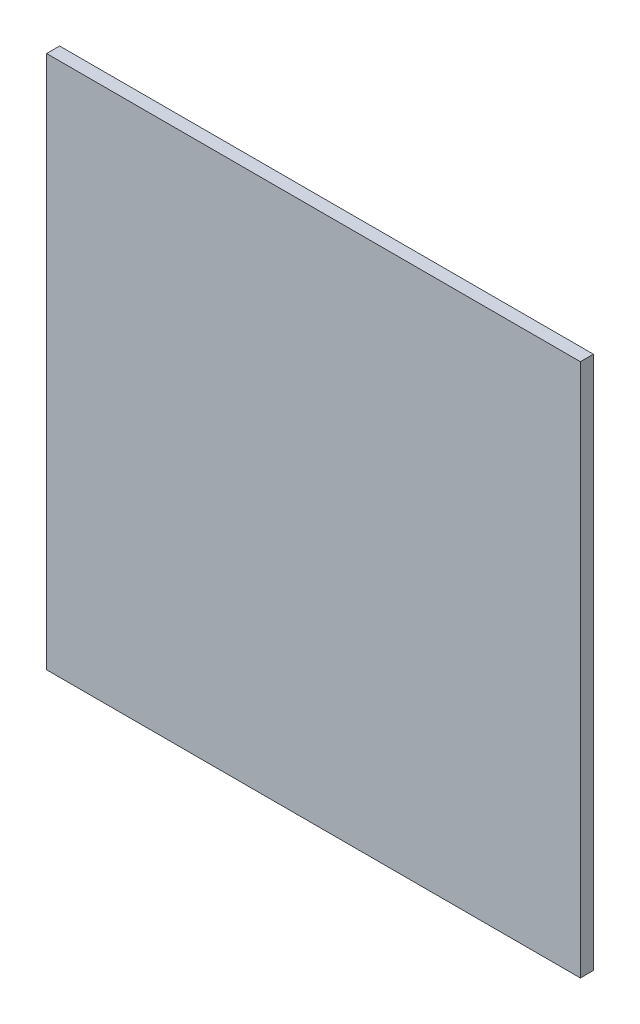
SolidWorks part; units mm, degrees
ref_plane "前基準面" through (0, 0, 0) normal (0, 0, 1) x (1, 0, 0)
ref_plane "上基準面" through (0, 0, 0) normal (0, 1, 0) x (1, 0, 0)
ref_plane "右基準面" through (0, 0, 0) normal (1, 0, 0) x (0, 0, -1)
sketch "草圖1" plane through (0, 0, 0) normal (0, 0, 1) x (1, 0, 0)
  line L1 (-205, 205) -> (205, 205)
  line L2 (-205, 205) -> (-205, -205)
  line L3 (-205, -205) -> (205, -205)
  line L4 (205, 205) -> (205, -205)
  line L5 (-205, 205) -> (205, -205) construction
  line L6 (-205, -205) -> (205, 205) construction
  point P0 (0, 0)
  dimension "D1" = 410
  dimension "D2" = 410
extrude "填料-伸長1" add sketch "草圖1" along normal blind 10
sketch "草圖2" plane through (0, 0, 10) normal (0, 0, 1) x (1, 0, 0)
  line L1 (-152.2141, 156.7714) -> (139.4536, 156.7714) construction
  line L2 (-152.2141, 156.7714) -> (-152.2141, -147.6568) construction
  line L3 (-152.2141, -147.6568) -> (139.4536, -147.6568) construction
  line L4 (139.4536, 156.7714) -> (139.4536, -147.6568) construction
